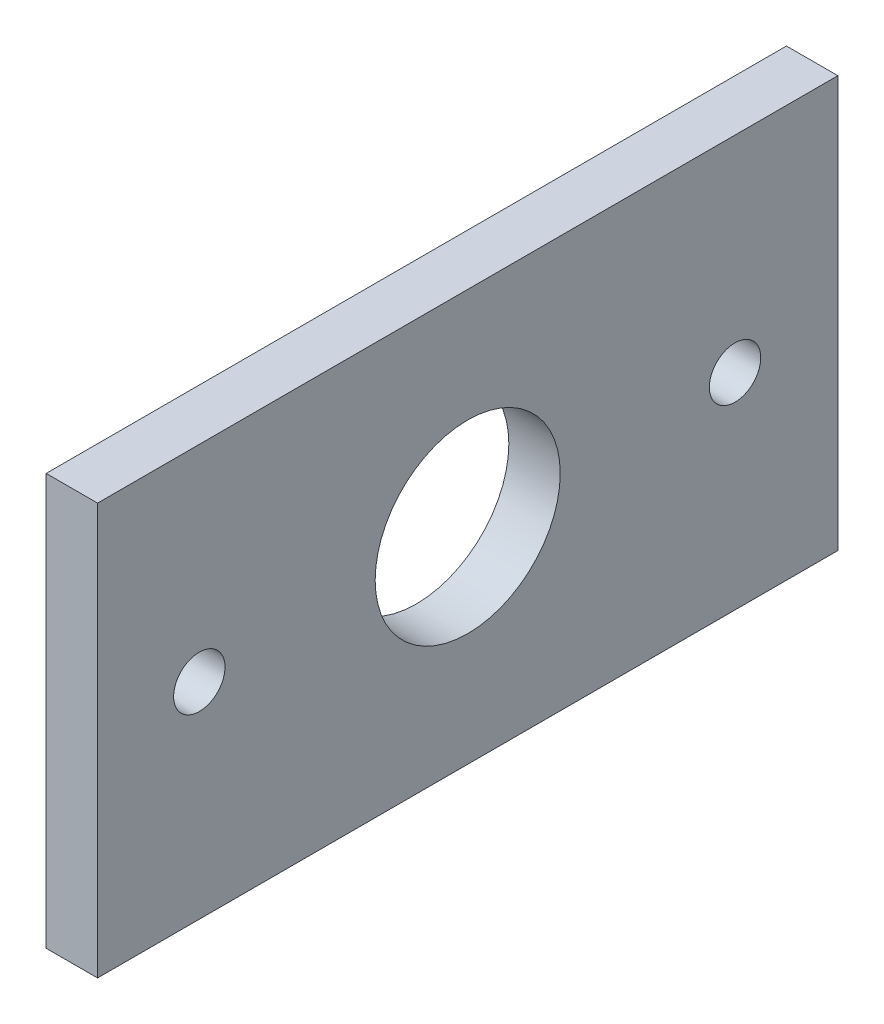
SolidWorks part; units mm, degrees
ref_plane "Front Plane" through (0, 0, 0) normal (0, 0, 1) x (1, 0, 0)
ref_plane "Top Plane" through (0, 0, 0) normal (0, 1, 0) x (1, 0, 0)
ref_plane "Right Plane" through (0, 0, 0) normal (1, 0, 0) x (0, 0, -1)
sketch "Sketch1" plane through (0, 0, 0) normal (1, 0, 0) x (0, 0, -1)
  line L0 (0, 0) -> (72, -40) construction
  line L1 (0, 0) -> (72, 0)
  line L2 (0, 0) -> (0, -40)
  line L3 (0, -40) -> (72, -40)
  line L4 (72, 0) -> (72, -40)
  line L5 (19.7925, 0) -> (0, -40) construction
  line L6 (52, 0) -> (72, -40) construction
  line L7 (52, 240) -> (52, -360) construction
  circle A0 centre (36, -20) radius 9
  circle A1 centre (9.8963, -20) radius 2.5
  circle A2 centre (62, -20) radius 2.5
  dimension "D3" = 18
  dimension "D4" = 5
  dimension "D5" = 5
  dimension "D1" = 72
  dimension "D2" = 40
extrude "Boss-Extrude1" add sketch "Sketch1" along normal blind 5
